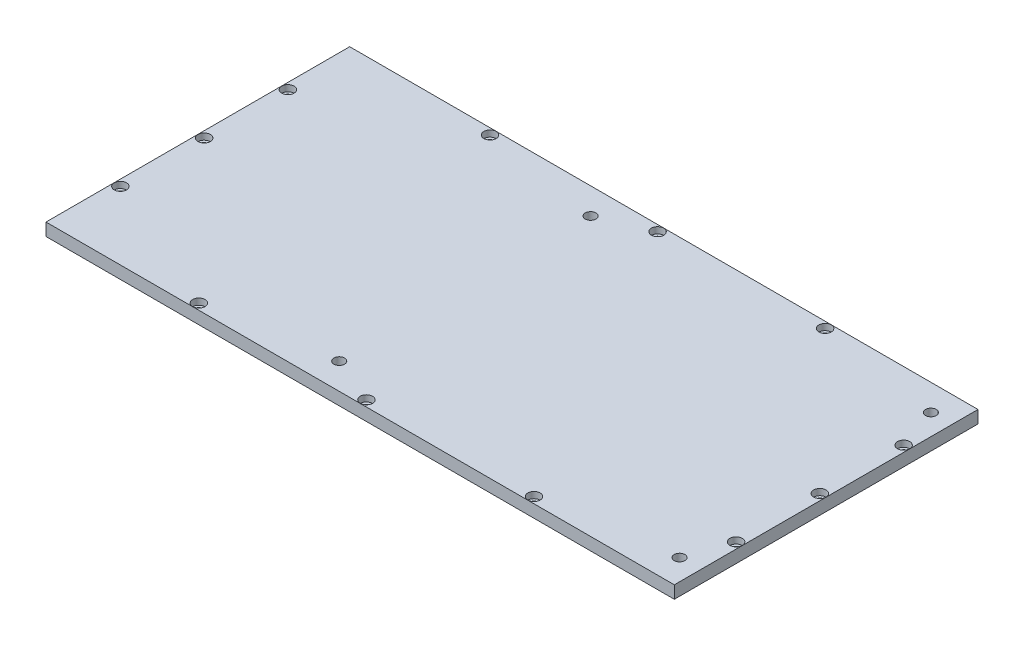
SolidWorks part; units mm, degrees
material "Polypropylene"
ref_plane "正面" through (0, 0, 0) normal (0, 0, 1) x (1, 0, 0)
ref_plane "平面" through (0, 0, 0) normal (0, 1, 0) x (1, 0, 0)
ref_plane "右側面" through (0, 0, 0) normal (1, 0, 0) x (0, 0, -1)
sketch "ｽｹｯﾁ1" plane through (0, 0, 0) normal (0, 1, 0) x (1, 0, 0)
  line L1 (-150, 72.5) -> (150, 72.5)
  line L2 (-150, 72.5) -> (-150, -72.5)
  line L3 (-150, -72.5) -> (150, -72.5)
  line L4 (150, 72.5) -> (150, -72.5)
  line L5 (-150, 72.5) -> (150, -72.5) construction
  line L6 (-150, -72.5) -> (150, 72.5) construction
  point P0 (0, 0)
  dimension "D1" = 300
  dimension "D2" = 145
extrude "ﾎﾞｽ - 押し出し1" add sketch "ｽｹｯﾁ1" along normal blind 60
shell "ｼｪﾙ1" thickness 6
sketch "ｽｹｯﾁ2" plane through (0, 6, 0) normal (0, 1, 0) x (1, 0, 0)
  line L0 (140, 72.5) -> (140, -72.5) construction
  line L1 (150, 72.5) -> (-150, 72.5) construction
  line L2 (-150, -72.5) -> (150, -72.5) construction
  line L3 (140, -72.5) -> (-22.5, -72.5) construction
  line L4 (-22.5, -72.5) -> (-22.5, 72.5) construction
  line L6 (150, -72.5) -> (150, 72.5) construction
  line L7 (-22.5, 0) -> (140, 0) construction
  line L8 (58.75, 72.5) -> (58.75, -72.5) construction
  circle A0 centre (140, 60) radius 2.55
  circle A1 centre (140, -60) radius 2.55
  circle A2 centre (-22.5, -60) radius 2.55
  circle A3 centre (-22.5, 60) radius 2.55
  point P18 (58.75, 0)
  dimension "D3" = 5.1
  dimension "D1" = 162.5
  dimension "D2" = 10
  dimension "D4" = 60
extrude "ｶｯﾄ - 押し出し1" cut sketch "ｽｹｯﾁ2" against normal through all
sketch "ｽｹｯﾁ3" plane through (0, 6, 0) normal (0, 1, 0) x (1, 0, 0)
  line L4 (150, -72.5) -> (150, 72.5)
  line L5 (150, 72.5) -> (-150, 72.5)
  line L6 (-150, 72.5) -> (-150, -72.5)
  line L7 (-150, -72.5) -> (150, -72.5)
  line L8 (150, -72.5) -> (150, 72.5)
  line L9 (150, 72.5) -> (-150, 72.5)
  line L10 (-150, 72.5) -> (-150, -72.5)
  line L11 (-150, -72.5) -> (150, -72.5)
  dimension "D1" = 0
extrude "ｶｯﾄ - 押し出し2" cut sketch "ｽｹｯﾁ3" along normal through all
sketch "ｽｹｯﾁ4" plane through (0, 0, 0) normal (0, -1, 0) x (1, 0, 0)
  line L0 (150, 72.5) -> (150, -72.5) construction
  line L1 (-147, 69.5) -> (147, 69.5) construction
  line L2 (-147, 69.5) -> (-147, -69.5) construction
  line L3 (-147, -69.5) -> (147, -69.5) construction
  line L4 (147, 69.5) -> (147, -69.5) construction
  line L5 (-147, 69.5) -> (147, -69.5) construction
  line L6 (-147, -69.5) -> (147, 69.5) construction
  line L7 (150, -72.5) -> (-150, -72.5) construction
  line L8 (-147, 0) -> (147, 0) construction
  line L10 (0, -69.5) -> (0, 69.5) construction
  circle A0 centre (147, 0) radius 1.6
  circle A1 centre (147, 40) radius 1.6
  circle A2 centre (147, -40) radius 1.6
  circle A3 centre (-147, -40) radius 1.6
  circle A4 centre (-147, 0) radius 1.6
  circle A5 centre (-147, 40) radius 1.6
  circle A6 centre (0, 69.5) radius 1.6
  circle A7 centre (-80, 69.5) radius 1.6
  circle A8 centre (80, 69.5) radius 1.6
  circle A9 centre (80, -69.5) radius 1.6
  circle A10 centre (0, -69.5) radius 1.6
  circle A11 centre (-80, -69.5) radius 1.6
  point P0 (0, 0)
  dimension "D3" = 3.2
  dimension "D5" = 80
  dimension "D1" = 3
  dimension "D2" = 3
  dimension "D4" = 40
extrude "ｶｯﾄ - 押し出し3" cut sketch "ｽｹｯﾁ4" against normal through all
sketch "ｽｹｯﾁ5" plane through (0, 6, 0) normal (0, 1, 0) x (1, 0, 0)
  circle A0 centre (147, -40) radius 2.95
  circle A1 centre (147, 0) radius 2.95
  circle A2 centre (147, 40) radius 2.95
  circle A3 centre (80, 69.5) radius 2.95
  circle A4 centre (0, 69.5) radius 2.95
  circle A5 centre (-80, 69.5) radius 2.95
  circle A6 centre (-147, 40) radius 2.95
  circle A7 centre (-147, 0) radius 2.95
  circle A8 centre (-147, -40) radius 2.95
  circle A9 centre (80, -69.5) radius 2.95
  circle A10 centre (0, -69.5) radius 2.95
  circle A11 centre (-80, -69.5) radius 2.95
  dimension "D1" = 5.9
extrude "ｶｯﾄ - 押し出し5" cut sketch "ｽｹｯﾁ5" against normal blind 3
